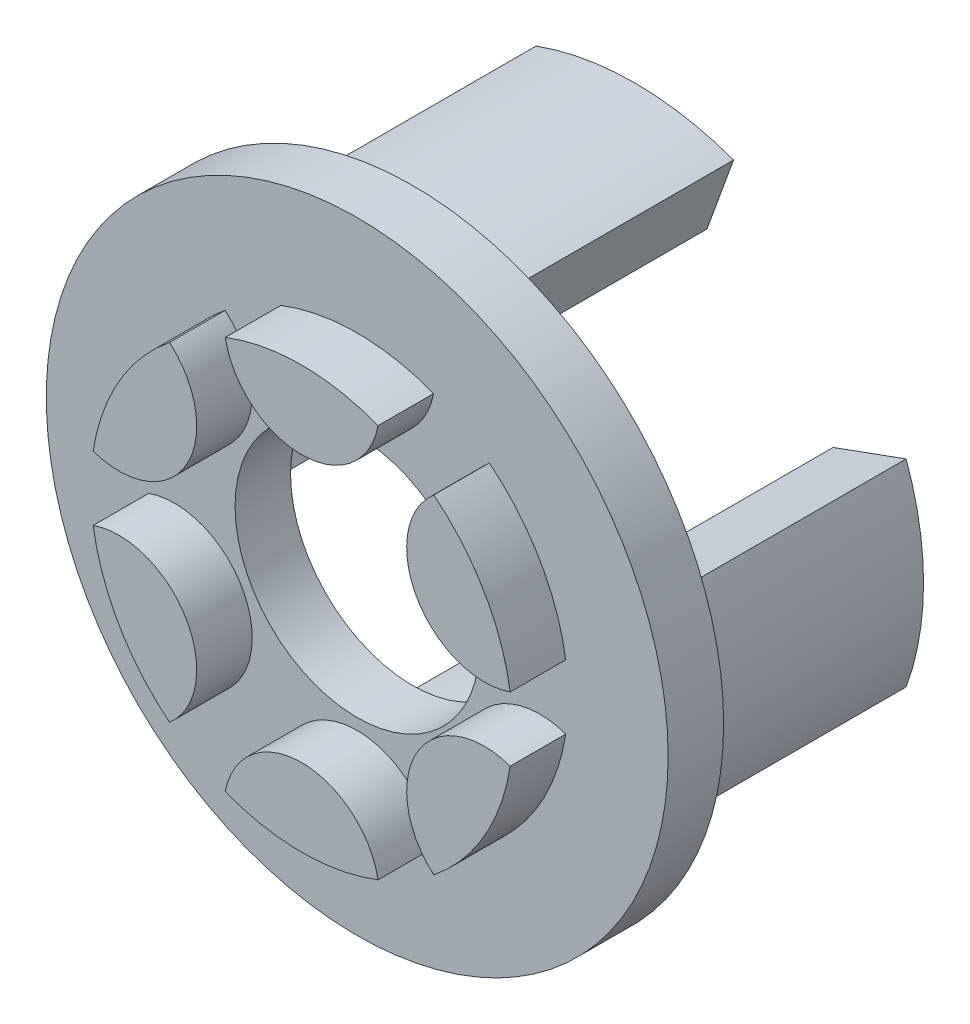
SolidWorks part; units mm, degrees
ref_plane "前视基准面" through (0, 0, 0) normal (0, 0, 1) x (1, 0, 0)
ref_plane "上视基准面" through (0, 0, 0) normal (0, 1, 0) x (1, 0, 0)
ref_plane "右视基准面" through (0, 0, 0) normal (1, 0, 0) x (0, 0, -1)
sketch "草图1" plane through (0, 0, 0) normal (0, 0, 1) x (1, 0, 0)
  circle A0 centre (0, 0) radius 28
  dimension "D1" = 56
extrude "凸台-拉伸1" add sketch "草图1" along normal blind 5
sketch "草图2" plane through (0, 0, 0) normal (0, 0, -1) x (-1, 0, 0)
  line L0 (-6.4984, 17.8542) -> (-8.8925, 24.432)
  line L1 (0, 19) -> (0, 26) construction
  line L2 (6.4984, 17.8542) -> (8.8925, 24.432)
  line L3 (0, 0) -> (-6.4984, 17.8542) construction
  line L4 (0, 0) -> (0, 19) construction
  line L5 (0, 0) -> (6.4984, 17.8542) construction
  line L6 (17.8542, 6.4984) -> (24.432, 8.8925)
  line L7 (17.8542, -6.4984) -> (24.432, -8.8925)
  line L8 (6.4984, -17.8542) -> (8.8925, -24.432)
  line L9 (-6.4984, -17.8542) -> (-8.8925, -24.432)
  line L10 (-17.8542, -6.4984) -> (-24.432, -8.8925)
  line L11 (-17.8542, 6.4984) -> (-24.432, 8.8925)
  arc A0 (8.8925, 24.432) -> (-8.8925, 24.432) centre (0, 0) ccw
  arc A1 (6.4984, 17.8542) -> (-6.4984, 17.8542) centre (0, 0) ccw
  arc A2 (-8.8925, 24.432) -> (8.8925, 24.432) centre (0, 0) ccw construction
  arc A3 (-6.4984, 17.8542) -> (6.4984, 17.8542) centre (0, 0) ccw construction
  arc A4 (24.432, -8.8925) -> (24.432, 8.8925) centre (0, 0) ccw
  arc A5 (17.8542, -6.4984) -> (17.8542, 6.4984) centre (0, 0) ccw
  arc A6 (-8.8925, -24.432) -> (8.8925, -24.432) centre (0, 0) ccw
  arc A7 (-6.4984, -17.8542) -> (6.4984, -17.8542) centre (0, 0) ccw
  arc A8 (-24.432, 8.8925) -> (-24.432, -8.8925) centre (0, 0) ccw
  arc A9 (-17.8542, 6.4984) -> (-17.8542, -6.4984) centre (0, 0) ccw
  point P23 (0, 0)
  dimension "D1" = 52
  dimension "D2" = 38
  dimension "D4" = 40
  dimension "D3" = 4
extrude "凸台-拉伸2" add sketch "草图2" along normal blind 20
sketch "草图3" plane through (0, 0, 0) normal (0, 0, -1) x (-1, 0, 0)
  circle A0 centre (0, 0) radius 11
  dimension "D1" = 22
extrude "切除-拉伸1" cut sketch "草图3" against normal blind 5
sketch "草图4" plane through (0, 0, 5) normal (0, 0, 1) x (1, 0, 0)
  arc A0 (-18.7779, 2.8968) -> (-18.7779, -2.8968) centre (0, 0) ccw construction
  arc A1 (-6.8802, 17.7105) -> (6.8802, 17.7105) centre (0, 19) ccw
  arc A2 (11.8977, 14.8137) -> (18.7779, 2.8968) centre (16.4545, 9.5) ccw construction
  arc A3 (11.8977, -14.8137) -> (18.7779, -2.8968) centre (16.4545, -9.5) ccw construction
  arc A4 (6.8802, -17.7105) -> (-6.8802, -17.7105) centre (0, -19) ccw construction
  arc A5 (-18.7779, -2.8968) -> (-11.8977, -14.8137) centre (-16.4545, -9.5) ccw construction
  arc A6 (-18.7779, 2.8968) -> (-11.8977, 14.8137) centre (-16.4545, 9.5) ccw construction
  arc A8 (-6.8802, 17.7105) -> (6.8802, 17.7105) centre (0, 0) cw
  arc A9 (6.8802, 17.7105) -> (-6.8802, 17.7105) centre (0, 19) ccw construction
  arc A10 (-11.8977, 14.8137) -> (-18.7779, 2.8968) centre (-16.4545, 9.5) ccw construction
  arc A11 (-11.8977, 14.8137) -> (-18.7779, 2.8968) centre (0, 0) ccw construction
  arc A12 (-11.8977, -14.8137) -> (-18.7779, -2.8968) centre (-16.4545, -9.5) ccw construction
  arc A13 (-18.7779, -2.8968) -> (-11.8977, -14.8137) centre (0, 0) ccw construction
  arc A14 (-11.8977, -14.8137) -> (-6.8802, -17.7105) centre (0, 0) ccw construction
  arc A15 (-6.8802, -17.7105) -> (6.8802, -17.7105) centre (0, -19) ccw construction
  arc A16 (6.8802, -17.7105) -> (11.8977, -14.8137) centre (0, 0) ccw construction
  arc A17 (11.8977, -14.8137) -> (18.7779, 2.8968) centre (0, 0) ccw construction
  arc A18 (18.7779, -2.8968) -> (11.8977, -14.8137) centre (16.4545, -9.5) ccw construction
  arc A19 (-6.8802, -17.7105) -> (6.8802, -17.7105) centre (0, 0) ccw construction
  arc A20 (18.7779, 2.8968) -> (11.8977, 14.8137) centre (16.4545, 9.5) ccw construction
  arc A21 (18.7779, 2.8968) -> (11.8977, 14.8137) centre (0, 0) ccw construction
  arc A22 (11.8977, 14.8137) -> (-11.8977, 14.8137) centre (0, 0) ccw construction
  arc A23 (11.8977, 14.8137) -> (18.7779, 2.8968) centre (16.4545, 9.5) ccw
  arc A24 (11.8977, 14.8137) -> (18.7779, 2.8968) centre (0, 0) cw
  arc A25 (18.7779, -2.8968) -> (11.8977, -14.8137) centre (16.4545, -9.5) ccw
  arc A26 (18.7779, -2.8968) -> (11.8977, -14.8137) centre (0, 0) cw
  arc A27 (6.8802, -17.7105) -> (-6.8802, -17.7105) centre (0, -19) ccw
  arc A28 (6.8802, -17.7105) -> (-6.8802, -17.7105) centre (0, 0) cw
  arc A29 (-11.8977, -14.8137) -> (-18.7779, -2.8968) centre (-16.4545, -9.5) ccw
  arc A30 (-11.8977, -14.8137) -> (-18.7779, -2.8968) centre (0, 0) cw
  arc A31 (-18.7779, 2.8968) -> (-11.8977, 14.8137) centre (-16.4545, 9.5) ccw
  arc A32 (-18.7779, 2.8968) -> (-11.8977, 14.8137) centre (0, 0) cw
  point P3 (0, 0)
  point P12 (0, 0)
  point P40 (0, 0)
  dimension "D2" = 14
  dimension "D1" = 38
  dimension "D3" = 6
extrude "凸台-拉伸4" add sketch "草图4" along normal blind 5
